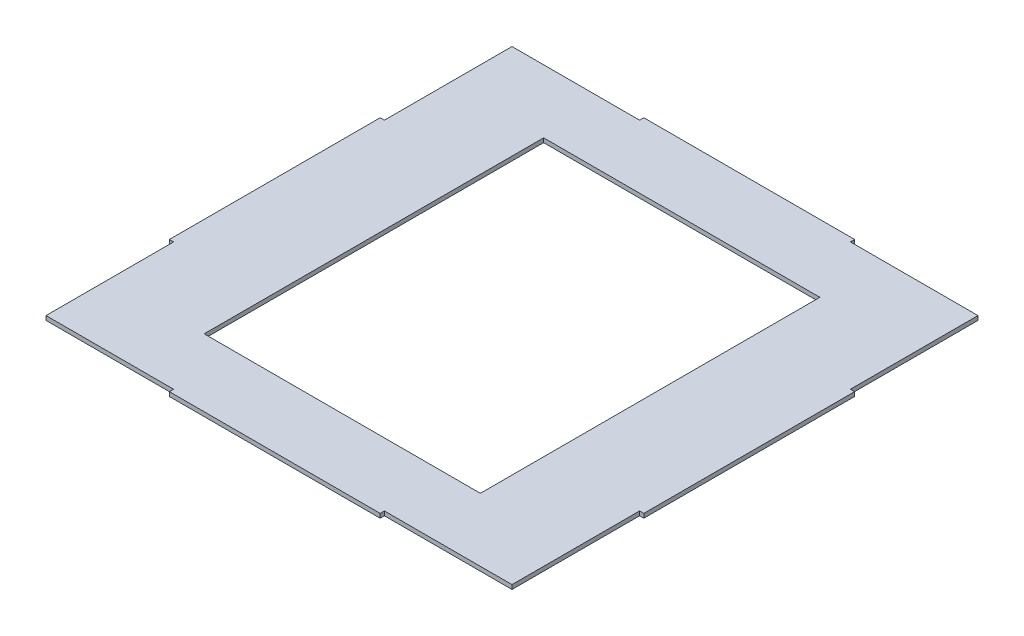
SolidWorks part; units mm, degrees
ref_plane "Front Plane" through (0, 0, 0) normal (0, 0, 1) x (1, 0, 0)
ref_plane "Top Plane" through (0, 0, 0) normal (0, 1, 0) x (1, 0, 0)
ref_plane "Right Plane" through (0, 0, 0) normal (1, 0, 0) x (0, 0, -1)
sketch "Sketch1" plane through (0, 0, 0) normal (0, 1, 0) x (1, 0, 0)
  line L0 (-221, 100) -> (-225, 100)
  line L1 (-225, 100) -> (-225, -100)
  line L2 (-225, -100) -> (-221, -100)
  line L3 (-221, -100) -> (-221, -221)
  line L4 (-221, -221) -> (-100, -221)
  line L5 (-100, -221) -> (-100, -225)
  line L6 (-100, -225) -> (100, -225)
  line L7 (100, -225) -> (100, -221)
  line L8 (100, -221) -> (221, -221)
  line L9 (221, -221) -> (221, -100)
  line L10 (221, -100) -> (225, -100)
  line L11 (225, -100) -> (225, 100)
  line L12 (225, 100) -> (221, 100)
  line L13 (221, 100) -> (221, 221)
  line L14 (221, 221) -> (100, 221)
  line L15 (100, 221) -> (100, 225)
  line L16 (100, 225) -> (-100, 225)
  line L17 (-100, 225) -> (-100, 221)
  line L18 (-100, 221) -> (-221, 221)
  line L19 (-221, 221) -> (-221, 100)
  line L26 (-131, -161) -> (131, -161)
  line L45 (-131, -161) -> (-131, 161)
  line L46 (-131, 161) -> (131, 161)
  line L47 (131, -161) -> (131, 161)
  line L48 (-131, -161) -> (131, 161) construction
  line L49 (-131, 161) -> (131, -161) construction
  point P20 (0, 0)
  point P21 (0, 0)
  dimension "D1" = 200
  dimension "D2" = 4
  dimension "D3" = 450
  dimension "D4" = 450
  dimension "D5" = 121
  dimension "D6" = 200
  dimension "D7" = 121
  dimension "D8" = 4
  dimension "D9" = 121
  dimension "D10" = 121
  dimension "D11" = 225
  dimension "D12" = 4
  dimension "D13" = 225
  dimension "D14" = 4
  dimension "D15" = 4
  dimension "D16" = 4
  dimension "D17" = 200
  dimension "D18" = 121
  dimension "D19" = 121
  dimension "D20" = 60
  dimension "D21" = 90
extrude "Boss-Extrude1" add sketch "Sketch1" along normal blind 4
